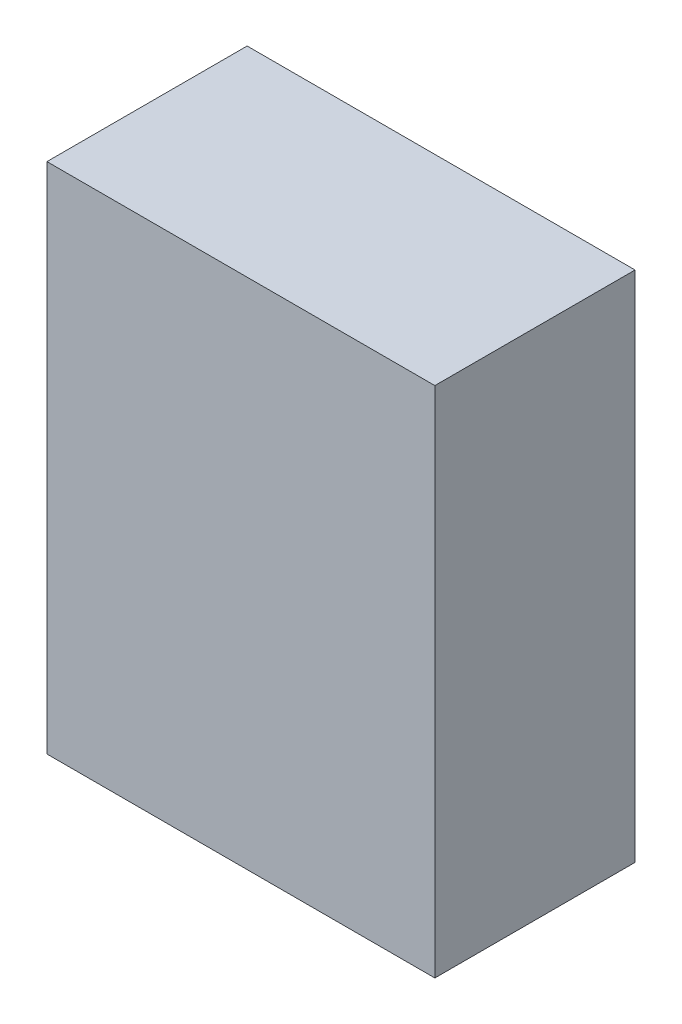
SolidWorks part; units mm, degrees
ref_plane "Alzado" through (0, 0, 0) normal (0, 0, 1) x (1, 0, 0)
ref_plane "Planta" through (0, 0, 0) normal (0, 1, 0) x (1, 0, 0)
ref_plane "Vista lateral" through (0, 0, 0) normal (1, 0, 0) x (0, 0, -1)
sketch "Croquis1" plane through (0, 0, 0) normal (0, 0, 1) x (1, 0, 0)
  line L0 (0, 0) -> (0, -400) construction
  line L1 (0, 0) -> (600, 0)
  line L2 (0, 0) -> (0, -800)
  line L3 (0, -800) -> (600, -800)
  line L4 (600, 0) -> (600, -800)
  line L5 (300, -400) -> (600, -400) construction
  line L11 (-10, 10) -> (610, 10)
  line L12 (-10, 10) -> (-10, -810)
  line L13 (-10, -810) -> (610, -810)
  line L14 (610, 10) -> (610, -810)
  line L15 (-10, 10) -> (610, -810) construction
  line L16 (-10, -810) -> (610, 10) construction
  dimension "D1" = 300
  dimension "D2" = 600
  dimension "D3" = 800
extrude "Saliente-Extruir1" add sketch "Croquis1" along normal blind 300
sketch "Croquis6" plane through (0, 0, 300) normal (0, 0, 1) x (1, 0, 0)
  line L1 (-10, 10) -> (610, 10)
  line L2 (-10, 10) -> (-10, -810)
  line L3 (-10, -810) -> (610, -810)
  line L4 (610, 10) -> (610, -810)
extrude "Saliente-Extruir4" add sketch "Croquis6" along normal blind 20
